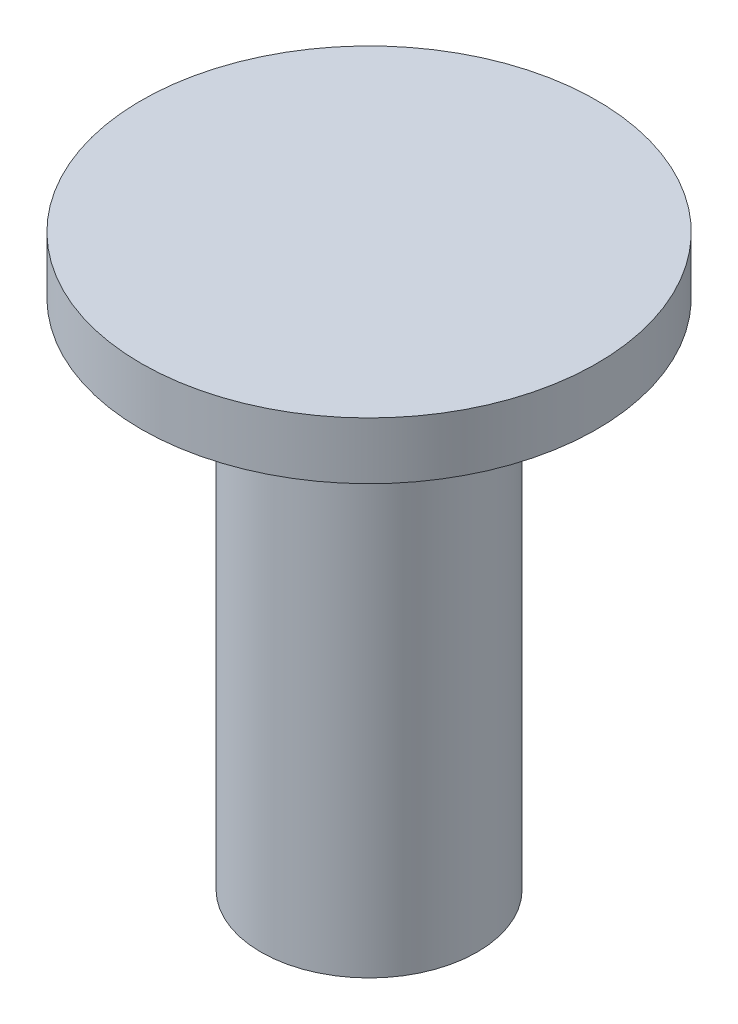
SolidWorks part; units mm, degrees
ref_plane "Front Plane" through (0, 0, 0) normal (0, 0, 1) x (1, 0, 0)
ref_plane "Top Plane" through (0, 0, 0) normal (0, 1, 0) x (1, 0, 0)
ref_plane "Right Plane" through (0, 0, 0) normal (1, 0, 0) x (0, 0, -1)
sketch "Эскиз1" plane through (0, 0, 0) normal (0, 1, 0) x (1, 0, 0)
  circle A0 centre (0, 0) radius 0.95
extrude "Бобышка-Вытянуть1" add sketch "Эскиз1" along normal blind 5
sketch "Эскиз3" plane through (0, 5, 0) normal (0, 1, 0) x (1, 0, 0)
  circle A0 centre (0, 0) radius 2
extrude "Бобышка-Вытянуть2" add sketch "Эскиз3" against normal blind 0.5
